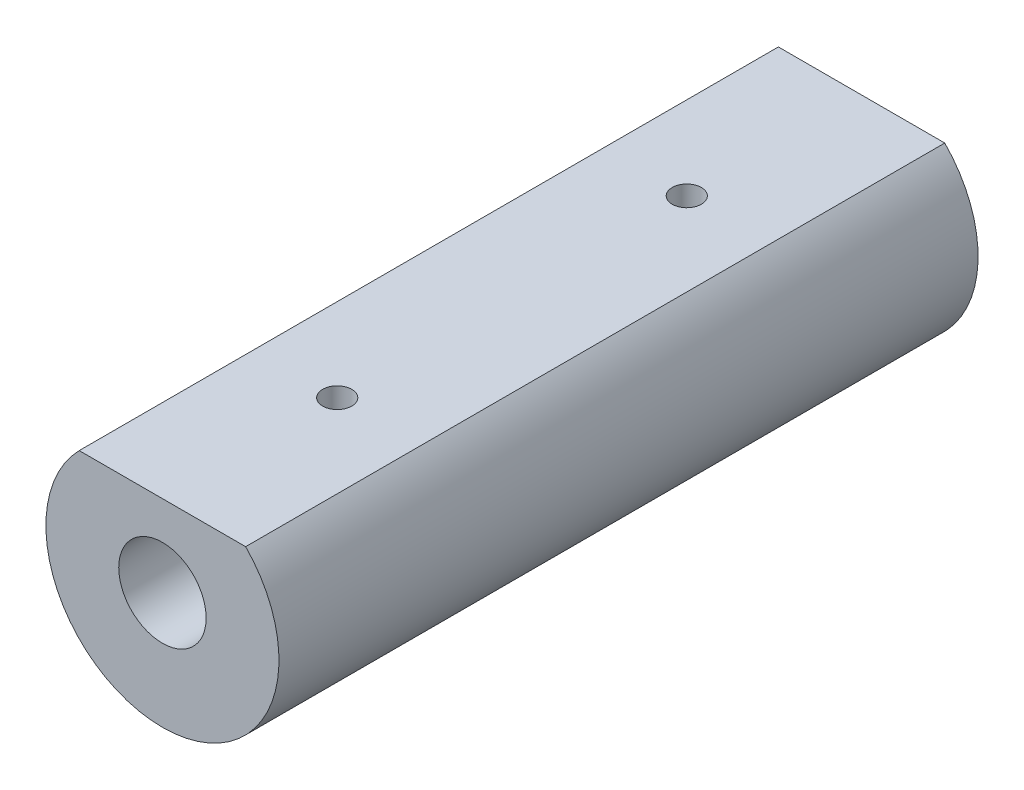
SolidWorks part; units mm, degrees
ref_plane "Front Plane" through (0, 0, 0) normal (0, 0, 1) x (1, 0, 0)
ref_plane "Top Plane" through (0, 0, 0) normal (0, 1, 0) x (1, 0, 0)
ref_plane "Right Plane" through (0, 0, 0) normal (1, 0, 0) x (0, 0, -1)
sketch "Sketch1" plane through (0, 0, 0) normal (0, 0, 1) x (1, 0, 0)
  circle A0 centre (0, 0) radius 10
  dimension "D1" = 20
extrude "Boss-Extrude1" add sketch "Sketch1" along normal blind 60
sketch "Sketch2" plane through (0, 0, 0) normal (0, 0, -1) x (-1, 0, 0)
  line L0 (-7.1414, 7) -> (7.1414, 7)
  circle A0 centre (0, 0) radius 10 construction
  arc A1 (-7.1414, 7) -> (7.1414, 7) centre (0, 0) cw
  circle A2 centre (0, 0) radius 3.75
  dimension "D2" = 7.5
  dimension "D1" = 7
extrude "Cut-Extrude1" cut sketch "Sketch2" against normal up to next
sketch "Sketch3" plane through (0, 7, 0) normal (0, 1, 0) x (1, 0, 0)
  line L2 (0, 0) -> (0, -60) construction
  line L3 (7.1414, 0) -> (-7.1414, 0) construction
  line L4 (7.1414, -60) -> (-7.1414, -60) construction
  circle A0 centre (0, -15) radius 1.25
  circle A1 centre (0, -45) radius 1.25
  point P6 (7.1414, -46.1595)
  dimension "D1" = 2.5
  dimension "D2" = 30
  dimension "D3" = 15
extrude "Cut-Extrude2" cut sketch "Sketch3" against normal up to next
